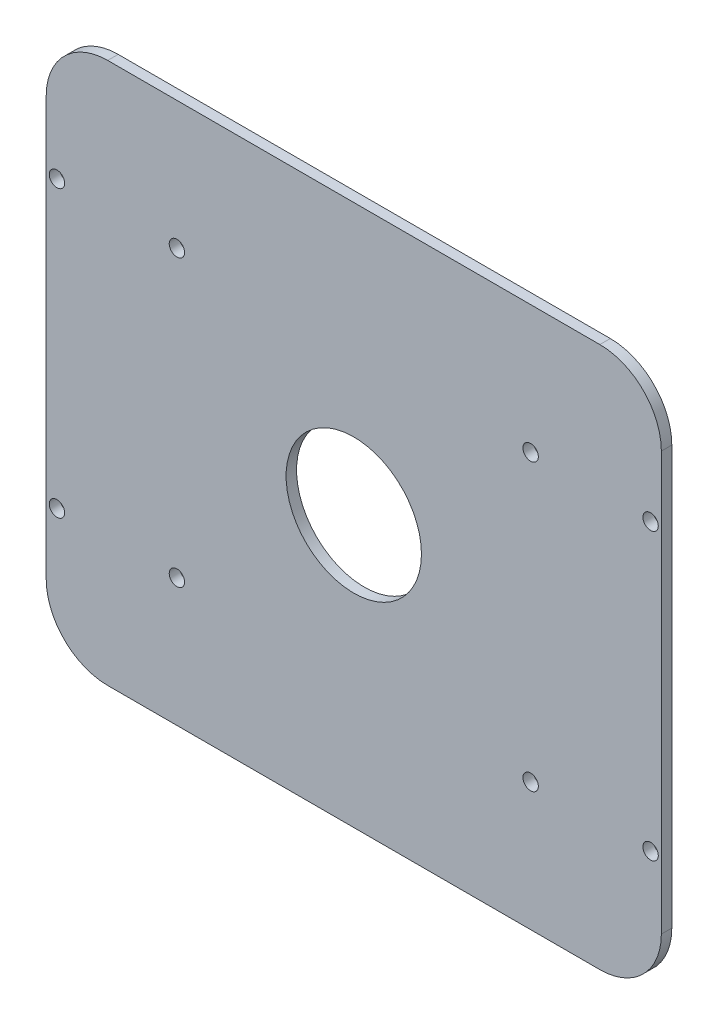
SolidWorks part; units mm, degrees
ref_plane "前视基准面" through (0, 0, 0) normal (0, 0, 1) x (1, 0, 0)
ref_plane "上视基准面" through (0, 0, 0) normal (0, 1, 0) x (1, 0, 0)
ref_plane "右视基准面" through (0, 0, 0) normal (1, 0, 0) x (0, 0, -1)
other "Configuration Table"
sketch "草图1" plane through (0, 0, 0) normal (0, 0, 1) x (1, 0, 0)
  line L0 (0, 0) -> (0, 29.8832) construction
  line L1 (-50, 44) -> (50, 44)
  line L2 (-50, 44) -> (-50, -44)
  line L3 (-50, -44) -> (50, -44)
  line L4 (50, 44) -> (50, -44)
  line L5 (-50, 44) -> (50, -44) construction
  line L6 (-50, -44) -> (50, 44) construction
  line L7 (0, 0) -> (36.2463, 0) construction
  circle A0 centre (-48.25, 23.2) radius 1.25
  circle A1 centre (-48.25, -23.2) radius 1.25
  circle A2 centre (48.25, -23.2) radius 1.25
  circle A3 centre (48.25, 23.2) radius 1.25
  circle A4 centre (0, 0) radius 11
  circle A5 centre (-28.75, 23.2) radius 1.25
  circle A6 centre (-28.75, -23.2) radius 1.25
  circle A7 centre (28.75, -23.2) radius 1.25
  circle A8 centre (28.75, 23.2) radius 1.25
  point P0 (0, 0)
  point P20 (0, 0)
  dimension "D3" = 2.5
  dimension "D4" = 2.5
  dimension "D8" = 22
  dimension "D9" = 2.5
  dimension "D1" = 88
  dimension "D2" = 100
  dimension "D5" = 1.75
  dimension "D6" = 23.2
  dimension "D7" = 23.2
  dimension "D10" = 19.5
extrude "凸台-拉伸1" add sketch "草图1" along normal blind 1.7
fillet "圆角1" radius 10 4 edges at (-50, -44, 0.85) (50, -44, 0.85) (50, 44, 0.85) (-50, 44, 0.85)
